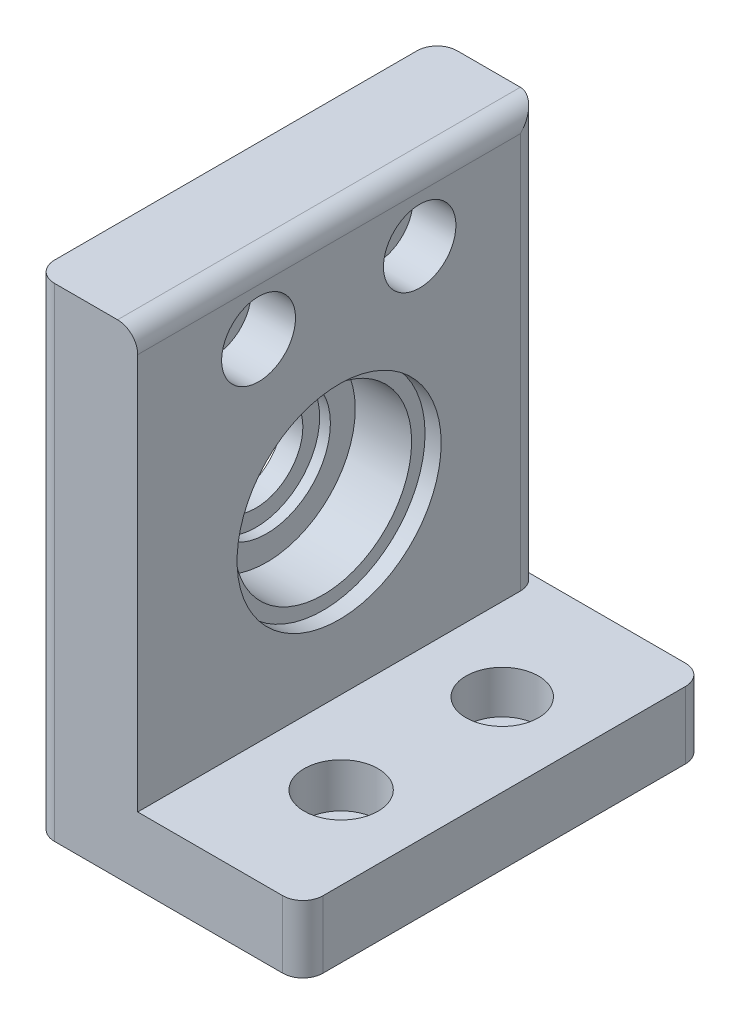
SolidWorks part; units mm, degrees
ref_plane "Front Plane" through (0, 0, 0) normal (0, 0, 1) x (1, 0, 0)
ref_plane "Top Plane" through (0, 0, 0) normal (0, 1, 0) x (1, 0, 0)
ref_plane "Right Plane" through (0, 0, 0) normal (1, 0, 0) x (0, 0, -1)
sketch "Sketch1" plane through (0, 0, 0) normal (0, 1, 0) x (1, 0, 0)
  line L1 (-10, -15) -> (10, -15)
  line L2 (-10, -15) -> (-10, 15)
  line L3 (-10, 15) -> (10, 15)
  line L4 (10, -15) -> (10, 15)
  line L5 (-10, -15) -> (10, 15) construction
  line L6 (-10, 15) -> (10, -15) construction
  point P0 (0, 0)
  dimension "D1" = 20
  dimension "D2" = 30
extrude "Boss-Extrude1" add sketch "Sketch1" along normal blind 5
sketch "Sketch2" plane through (0, 5, 0) normal (0, 1, 0) x (1, 0, 0)
  line L0 (10, 15) -> (-10, 15) construction
  line L1 (-10, -15) -> (-2.3, -15)
  line L2 (-10, -15) -> (-10, 15)
  line L3 (-10, 15) -> (-2.3, 15)
  line L4 (-2.3, -15) -> (-2.3, 15)
  dimension "D1" = 7.7
extrude "Boss-Extrude2" add sketch "Sketch2" along normal blind 25
sketch "Sketch3" plane through (-2.3, 0, 0) normal (1, 0, 0) x (0, 0, -1)
  line L0 (0, 30) -> (0, 5) construction
  line L1 (-15, 30) -> (15, 30) construction
  line L2 (-15, 5) -> (15, 5) construction
  circle A0 centre (0, 17.5) radius 3.5
  dimension "D1" = 7
extrude "Cut-Extrude1" cut sketch "Sketch3" against normal through all both and the other way through all
sketch "Sketch4" plane through (-2.3, 0, 0) normal (1, 0, 0) x (0, 0, -1)
  circle A0 centre (0, 17.5) radius 7.6
  dimension "D1" = 15.2
extrude "Cut-Extrude2" cut sketch "Sketch4" against normal blind 1.2
sketch "Sketch5" plane through (-3.5, 0, 0) normal (1, 0, 0) x (0, 0, -1)
  circle A0 centre (0, 17.5) radius 6.6
  dimension "D1" = 13.2
extrude "Cut-Extrude3" cut sketch "Sketch5" against normal blind 4.2
sketch "Sketch6" plane through (-7.7, 0, 0) normal (1, 0, 0) x (0, 0, -1)
  circle A0 centre (0, 17.5) radius 4.75
  dimension "D1" = 9.5
extrude "Cut-Extrude4" cut sketch "Sketch6" against normal blind 0.8
sketch "Sketch7" plane through (0, 5, 0) normal (0, 1, 0) x (1, 0, 0)
  line L0 (3.85, 15) -> (3.85, -15) construction
  line L1 (10, 15) -> (-2.3, 15) construction
  line L2 (-2.3, -15) -> (10, -15) construction
  line L3 (-2.3, 0) -> (10, 0) construction
  line L4 (-2.3, -15) -> (-2.3, 15) construction
  line L5 (10, -15) -> (10, 15) construction
  circle A0 centre (3.85, 6) radius 1.65
  circle A1 centre (3.85, -6) radius 1.7
  point P16 (0, 0)
  dimension "D1" = 3.3
  dimension "D2" = 3.4
  dimension "D3" = 12
extrude "Cut-Extrude5" cut sketch "Sketch7" against normal through all both and the other way through all
sketch "Sketch8" plane through (0, 5, 0) normal (0, 1, 0) x (1, 0, 0)
  circle A0 centre (3.85, 6) radius 2.7
  dimension "D1" = 5.4
extrude "Cut-Extrude6" cut sketch "Sketch8" against normal blind 3.2
sketch "Sketch9" plane through (0, 5, 0) normal (0, 1, 0) x (1, 0, 0)
  circle A0 centre (3.85, -6) radius 2.75
  dimension "D1" = 5.5
extrude "Cut-Extrude7" cut sketch "Sketch9" against normal blind 3.3
sketch "Sketch10" plane through (0, 30, 0) normal (0, 1, 0) x (1, 0, 0)
  line L1 (-10, 15) -> (-2.3, 15)
  line L2 (-10, 15) -> (-10, -15)
  line L3 (-10, -15) -> (-2.3, -15)
  line L4 (-2.3, 15) -> (-2.3, -15)
extrude "Boss-Extrude3" add sketch "Sketch10" along normal blind 6
sketch "Sketch11" plane through (-2.3, 0, 0) normal (1, 0, 0) x (0, 0, -1)
  line L0 (-15, 31) -> (15, 31) construction
  line L1 (-15, 36) -> (-15, 5) construction
  line L2 (15, 36) -> (15, 5) construction
  line L3 (-15, 36) -> (15, 36) construction
  line L4 (0, 36) -> (0, 0) construction
  circle A0 centre (-6, 31) radius 1.7
  circle A1 centre (6, 31) radius 1.65
  point P15 (0, 0)
  dimension "D2" = 3.4
  dimension "D3" = 3.3
  dimension "D1" = 5
  dimension "D4" = 12
extrude "Cut-Extrude8" cut sketch "Sketch11" against normal through all both and the other way through all
sketch "Sketch12" plane through (-2.3, 0, 0) normal (1, 0, 0) x (0, 0, -1)
  circle A0 centre (6, 31) radius 2.7
  dimension "D1" = 5.4
extrude "Cut-Extrude9" cut sketch "Sketch12" against normal blind 3.2
sketch "Sketch13" plane through (-2.3, 0, 0) normal (1, 0, 0) x (0, 0, -1)
  circle A0 centre (-6, 31) radius 2.75
  dimension "D1" = 5.5
extrude "Cut-Extrude10" cut sketch "Sketch13" against normal blind 3.3
sketch "Sketch14" plane through (-10, 0, 0) normal (-1, 0, 0) x (0, 0, 1)
  circle A0 centre (0, 17.5) radius 9.525 construction
  circle A1 centre (-9.525, 17.5) radius 1.5
  circle A2 centre (9.525, 17.5) radius 1.5
  dimension "D1" = 19.05
  dimension "D2" = 3
extrude "Cut-Extrude11" cut sketch "Sketch14" against normal blind 4.5
chamfer "Chamfer1" distance 0.75 angle 45 2 edges at (-10, 17.5, 11.025) (-10, 17.5, -8.025)
fillet "Fillet1" radius 1.5 6 edges at (-2.3, 20.5, -15) (-10, 18, 15) (10, 2.5, 15) (10, 2.5, -15) (-10, 18, -15) (-2.3, 36, 0)
